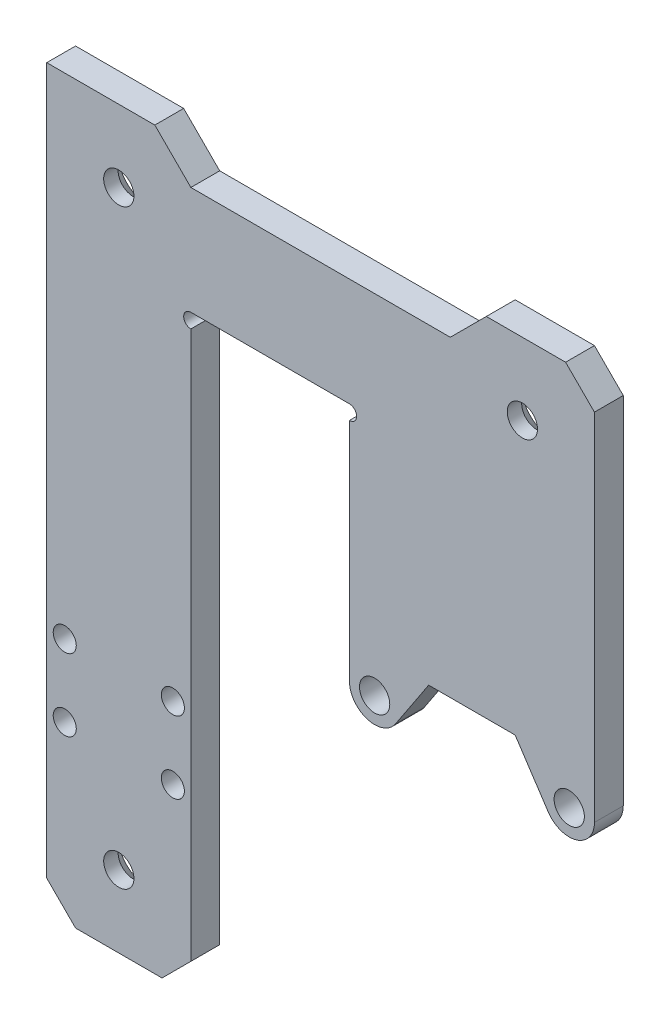
SolidWorks part; units mm, degrees
ref_plane "前视基准面" through (0, 0, 0) normal (0, 0, 1) x (1, 0, 0)
ref_plane "上视基准面" through (0, 0, 0) normal (0, 1, 0) x (1, 0, 0)
ref_plane "右视基准面" through (0, 0, 0) normal (1, 0, 0) x (0, 0, -1)
sketch "草图1" plane through (0, 0, 0) normal (0, 0, 1) x (1, 0, 0)
  line L0 (11, 0) -> (-11, 0)
  line L1 (11, 0) -> (11, -33.3066)
  line L3 (45, -33.3066) -> (45, 20)
  line L4 (45, 20) -> (-31, 20)
  line L5 (-31, 20) -> (-31, -82)
  line L6 (-11, 0) -> (-11, -82)
  line L7 (-31, -82) -> (-11, -82)
  line L8 (-21, -82) -> (-21, 20) construction
  line L9 (28, -37.8238) -> (28, 20) construction
  line L10 (17.4199, -35.2364) -> (22, -28.3066)
  line L11 (38.78, -72.4) -> (17.22, -72.4) construction
  line L12 (47, -64.18) -> (47, -45.22) construction
  line L13 (38.78, -37) -> (17.22, -37) construction
  line L14 (9, -64.18) -> (9, -45.22) construction
  line L15 (47, -72.4) -> (9, -37) construction
  line L16 (47, -37) -> (9, -72.4) construction
  line L17 (22, -28.3066) -> (34, -28.3066)
  line L18 (38.5801, -35.2364) -> (34, -28.3066)
  line L19 (-11, -22) -> (11, -22) construction
  circle A0 centre (-21, 10) radius 2.1
  circle A1 centre (35, 10) radius 2.1
  circle A2 centre (14.5, -33.3066) radius 2.1
  circle A3 centre (41.5, -33.3066) radius 2.1
  arc A4 (11, -33.3066) -> (17.4199, -35.2364) centre (14.5, -33.3066) ccw
  arc A5 (38.5801, -35.2364) -> (45, -33.3066) centre (41.5, -33.3066) ccw
  arc A6 (17.22, -72.4) -> (9, -64.18) centre (17.22, -64.18) cw construction
  arc A7 (38.78, -72.4) -> (47, -64.18) centre (38.78, -64.18) ccw construction
  arc A8 (47, -45.22) -> (38.78, -37) centre (38.78, -45.22) ccw construction
  arc A9 (17.22, -37) -> (9, -45.22) centre (17.22, -45.22) ccw construction
  circle A10 centre (14.5, -33.3066) radius 4 construction
  circle A11 centre (41.5, -33.3066) radius 4 construction
  circle A12 centre (-21, -72) radius 2.1
  point P0 (28, -54.7)
  point P4 (0, 0)
  point P47 (28, -28.3066)
  dimension "D5" = 4.2
  dimension "D6" = 10
  dimension "D8" = 37
  dimension "D9" = 3.5
  dimension "D10" = 3.5
  dimension "D11" = 4.2
  dimension "D12" = 38
  dimension "D2" = 34
  dimension "D14" = 8.22
  dimension "D15" = 8
  dimension "D20" = 10
  dimension "D21" = 10
  dimension "D3" = 49
  dimension "D4" = 22
  dimension "D7" = 20
  dimension "D13" = 35.4
  dimension "D16" = 6
  dimension "D17" = 5
  dimension "D18" = 22
  dimension "D19" = 60
extrude "凸台-拉伸1" add sketch "草图1" along normal mid plane 4
sketch "草图3" plane through (0, 0, 2) normal (0, 0, 1) x (1, 0, 0)
  line L0 (-16, 20) -> (-11, 15)
  line L1 (45, 20) -> (-31, 20) construction
  line L2 (-11, 15) -> (25, 15)
  line L3 (25, 15) -> (30, 20)
  line L4 (-11, 0) -> (11, 0) construction
  line L5 (-16, 20) -> (30, 20)
  circle A0 centre (-21, 10) radius 2.1 construction
  circle A1 centre (35, 10) radius 2.1 construction
  dimension "D1" = 15
  dimension "D2" = 10
  dimension "D3" = 45
  dimension "D4" = 10
extrude "切除-拉伸1" cut sketch "草图3" against normal through all
chamfer "倒角1" distance 2 angle 45 3 edges at (37.1, 10, -2) (-18.9, 10, -2) (-18.9, -72, -2)
sketch "草图4" plane through (0, 0, 2) normal (0, 0, 1) x (1, 0, 0)
  line L0 (-11, -82) -> (-11, 0) construction
  line L1 (11, 0) -> (11, -33.3066) construction
  circle A0 centre (-11, -1) radius 1
  circle A1 centre (11, -1) radius 1
  dimension "D1" = 2
extrude "切除-拉伸2" cut sketch "草图4" against normal through all
chamfer "倒角2" distance 4 angle 45 3 edges at (45, 20, 0) (-31, -82, 0) (-11, -82, 0)
sketch "草图7" plane through (0, 0, 2) normal (0, 0, 1) x (1, 0, 0)
  line L0 (-27, -82) -> (-15, -82) construction
  line L1 (-13.5, -58) -> (-28.5, -58) construction
  line L2 (-13.5, -58) -> (-13.5, -48) construction
  line L3 (-13.5, -48) -> (-28.5, -48) construction
  line L4 (-28.5, -58) -> (-28.5, -48) construction
  line L5 (-13.5, -58) -> (-28.5, -48) construction
  line L6 (-13.5, -48) -> (-28.5, -58) construction
  circle A1 centre (-28.5, -48) radius 1.6
  circle A2 centre (-28.5, -58) radius 1.6
  circle A3 centre (-13.5, -48) radius 1.6
  circle A4 centre (-13.5, -58) radius 1.6
  circle A5 centre (-21, -72) radius 2.1 construction
  point P0 (-21, -53)
  point P8 (-21, -82)
  dimension "D4" = 3.2
  dimension "D1" = 15
  dimension "D2" = 10
  dimension "D3" = 19
extrude "切除-拉伸3" cut sketch "草图7" against normal through all
